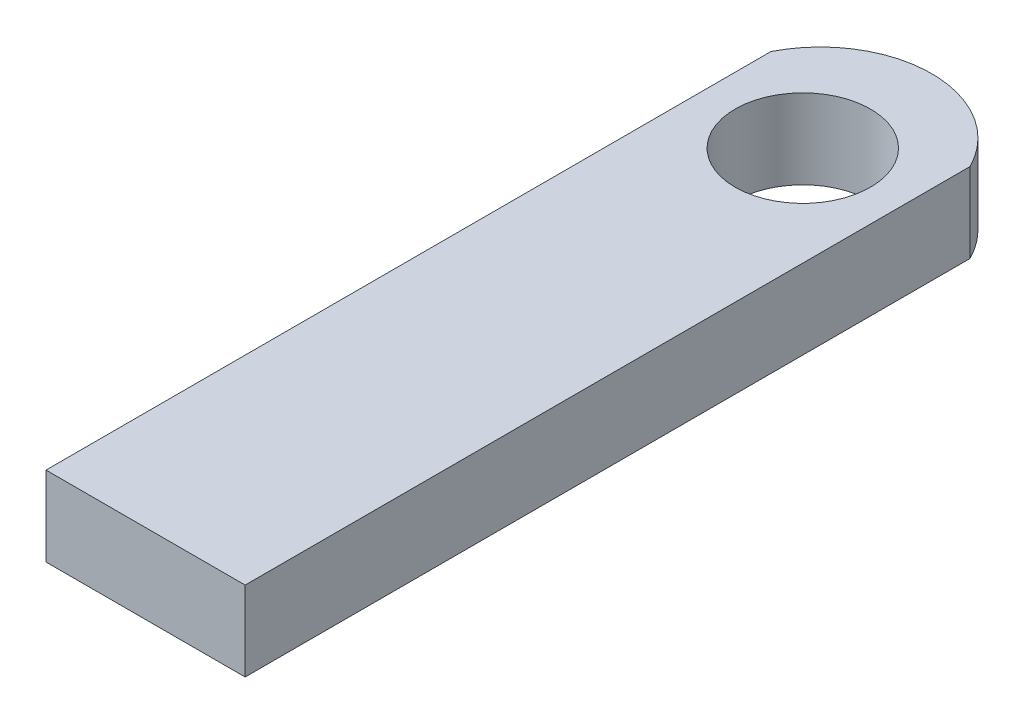
SolidWorks part; units mm, degrees
ref_plane "Front Plane" through (0, 0, 0) normal (0, 0, 1) x (1, 0, 0)
ref_plane "Top Plane" through (0, 0, 0) normal (0, 1, 0) x (1, 0, 0)
ref_plane "Right Plane" through (0, 0, 0) normal (1, 0, 0) x (0, 0, -1)
sketch "Sketch1" plane through (0, 0, 0) normal (0, 1, 0) x (1, 0, 0)
  line L0 (0, 0) -> (-5, 0)
  line L1 (-5, 0) -> (-5, 18.2)
  line L2 (-2.5, 16.939) -> (-2.5, 16.5) construction
  line L3 (0, 18.2) -> (0, 0)
  line L4 (-5, 18.2) -> (0, 18.2) construction
  arc A0 (-5, 18.2) -> (0, 18.2) centre (-2.5, 16.939) cw
  circle A2 centre (-2.5, 16.5) radius 1.7
  dimension "D2" = 3.4
  dimension "D3" = 2.8
  dimension "D1" = 5
  dimension "D5" = 16.5
extrude "Boss-Extrude1" add sketch "Sketch1" along normal blind 2
